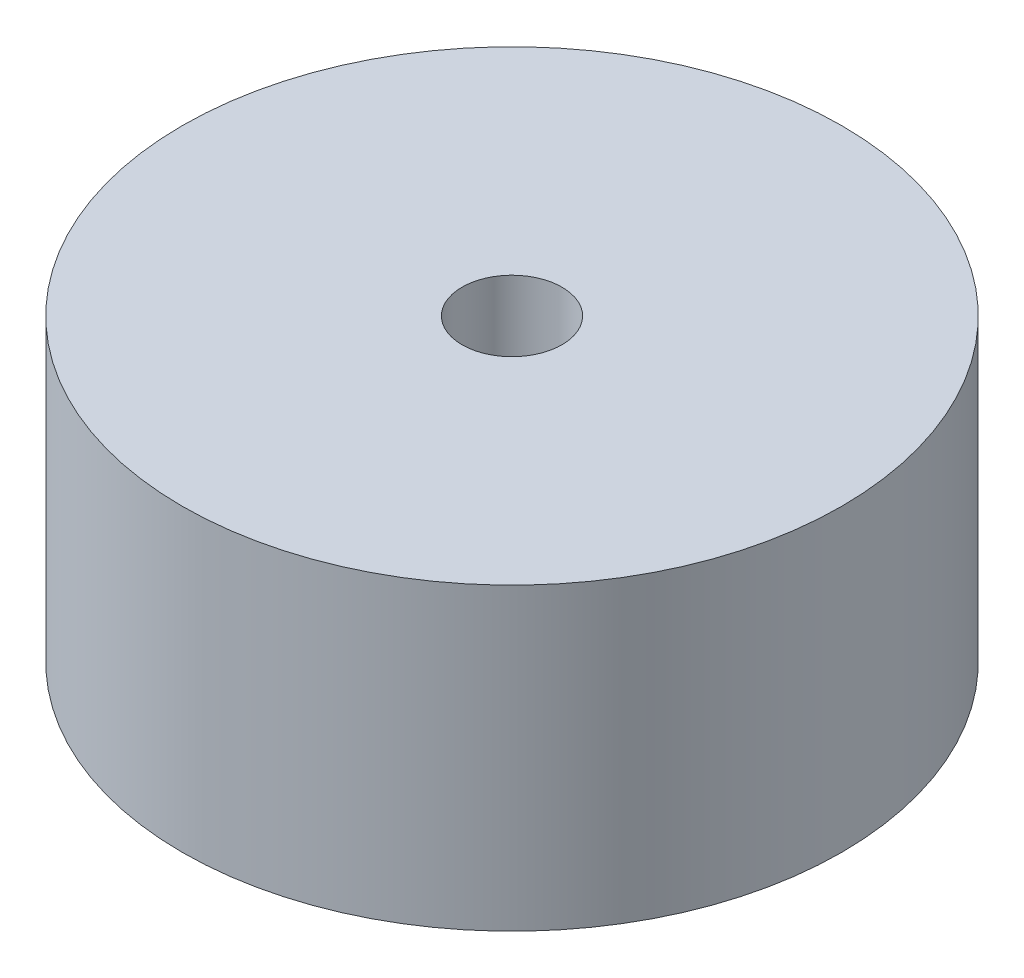
SolidWorks part; units mm, degrees
ref_plane "Front Plane" through (0, 0, 0) normal (0, 0, 1) x (1, 0, 0)
ref_plane "Top Plane" through (0, 0, 0) normal (0, 1, 0) x (1, 0, 0)
ref_plane "Right Plane" through (0, 0, 0) normal (1, 0, 0) x (0, 0, -1)
sketch "Sketch1" plane through (0, 0, 0) normal (0, 1, 0) x (1, 0, 0)
  circle A0 centre (0, 0) radius 33
  circle A1 centre (0, 0) radius 5
  dimension "D1" = 66
  dimension "D2" = 10
extrude "Boss-Extrude1" add sketch "Sketch1" along normal blind 30
